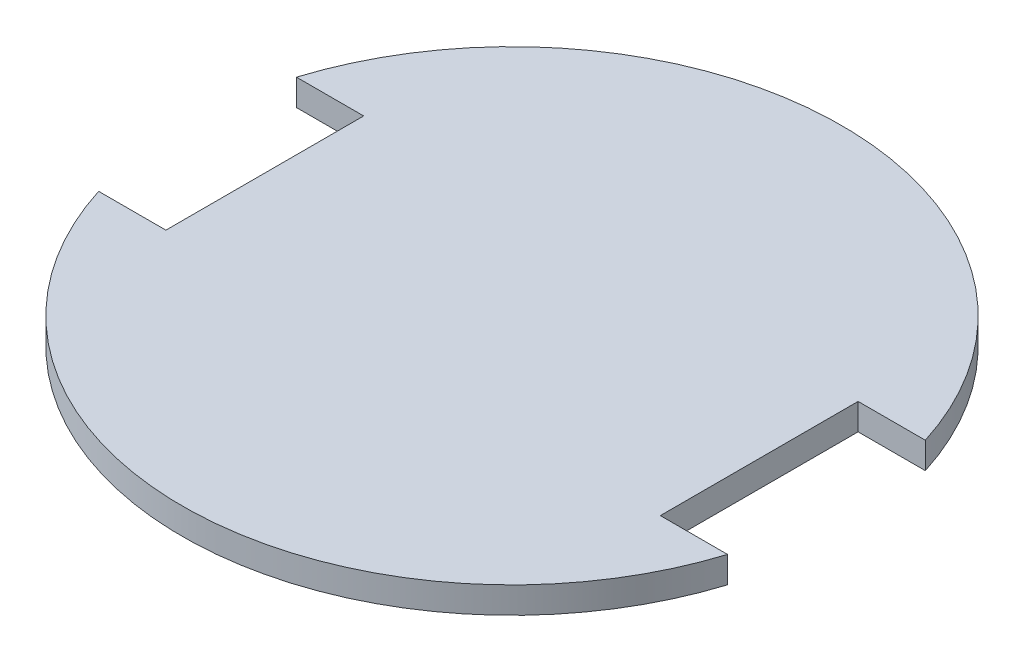
SolidWorks part; units mm, degrees
ref_plane "Plan de face" through (0, 0, 0) normal (0, 0, 1) x (1, 0, 0)
ref_plane "Plan de dessus" through (0, 0, 0) normal (0, 1, 0) x (1, 0, 0)
ref_plane "Plan de droite" through (0, 0, 0) normal (1, 0, 0) x (0, 0, -1)
sketch "Esquisse1" plane through (0, 0, 0) normal (0, 1, 0) x (1, 0, 0)
  line L0 (-75, -66.1438) -> (-75, 66.1438) construction
  line L1 (-75, 30) -> (-75, -30)
  line L2 (-100, 0) -> (100, 0) construction
  line L3 (-75, 30) -> (-95.3939, 30)
  line L4 (-75, -30) -> (-95.3939, -30)
  line L5 (0, 100) -> (0, -100) construction
  line L6 (75, -30) -> (95.3939, -30)
  line L7 (75, 30) -> (75, -30)
  line L8 (75, 30) -> (95.3939, 30)
  circle A0 centre (0, 0) radius 100 construction
  arc A1 (-95.3939, 30) -> (95.3939, 30) centre (0, 0) cw
  arc A2 (95.3939, -30) -> (-95.3939, -30) centre (0, 0) cw
  dimension "D1" = 75
  dimension "D2" = 30
  dimension "D3" = 60
extrude "Boss.-Extru.1" add sketch "Esquisse1" along normal blind 8
